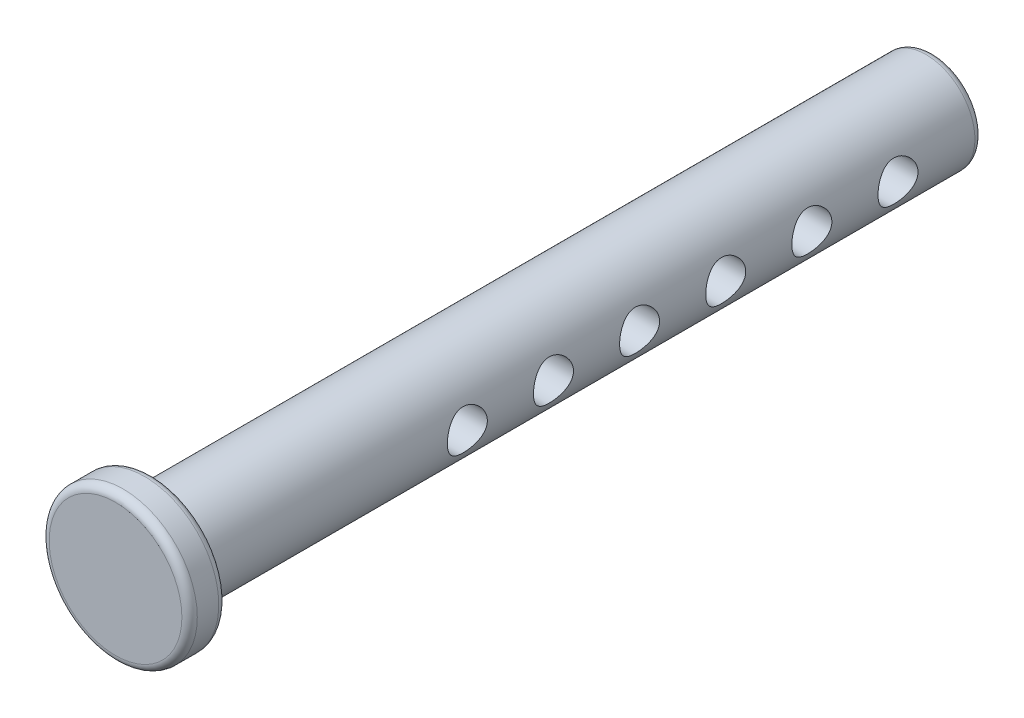
SolidWorks part; units mm, degrees
ref_plane "Front Plane" through (0, 0, 0) normal (1, 0, 0) x (0, 1, 0)
ref_plane "Top Plane" through (0, 0, 0) normal (0, 0, 1) x (0, 1, 0)
ref_plane "Right Plane" through (0, 0, 0) normal (0, 1, 0) x (-1, 0, 0)
sketch "Sketch1" plane through (0, 0, 0) normal (1, 0, 0) x (0, 1, 0)
  line L0 (0, 0) -> (4.815, 0)
  line L1 (4.815, 0) -> (4.815, -2.4)
  line L2 (4.815, -2.4) -> (3.175, -2.4)
  line L3 (3.175, -2.4) -> (3.175, -53.2)
  line L4 (3.175, -53.2) -> (0, -53.2)
  line L5 (0, -53.2) -> (0, 0)
  line L6 (0, -335.5768) -> (0, 16305.0472) construction
  dimension "D1" = 6.35
  dimension "D2" = 50.8
  dimension "D3" = 1.64
  dimension "D4" = 2.4
revolve "Revolve1" add sketch "Sketch1" angle 360 about L6
sketch "Sketch2" plane through (0, 0, 0) normal (1, 0, 0) x (0, 1, 0)
  line L0 (0, -47.7) -> (0, -42.1) construction
  line L1 (0, -42.1) -> (0, -36.5) construction
  line L2 (0, -36.5) -> (0, -30.9) construction
  line L3 (0, -30.9) -> (0, -25.3) construction
  line L4 (0, -25.3) -> (0, -19.7) construction
  line L5 (0, -47.7) -> (0, -49) construction
  line L6 (-3.175, -53.2) -> (3.175, -53.2) construction
  circle A0 centre (0, -47.7) radius 1.3
  circle A1 centre (0, -42.1) radius 1.3
  circle A3 centre (0, -25.3) radius 1.3
  circle A4 centre (0, -30.9) radius 1.3
  circle A6 centre (0, -36.5) radius 1.3
  circle A7 centre (0, -19.7) radius 1.3
  point P11 (0, -46.4)
  point P14 (0, -43.4)
  dimension "D1" = 2.6
  dimension "D2" = 4.2
  dimension "D3" = 3
extrude "Cut-Extrude1" cut sketch "Sketch2" against normal through all both and the other way through all
fillet "f7f" radius 0.5 2 edges at (-4.815, 0, -2.4) (-4.815, 0, 0)
fillet "Fillet2" radius 0.5 1 edges at (-3.175, 0, -53.2)
sketch "Sketch3" [suppressed] plane through (0, 0, 0) normal (1, 0, 0) x (0, 1, 0)
  line L0 (-3.175, -2.4) -> (-3.175, -52.7) construction
  line L1 (-3.175, -28.1) -> (3.175, -28.1)
  line L2 (-3.175, -28.1) -> (-3.175, -53.2)
  line L3 (-3.175, -53.2) -> (3.175, -53.2)
  line L4 (3.175, -28.1) -> (3.175, -53.2)
  line L5 (3.175, -52.7) -> (3.175, -2.4) construction
  line L6 (-2.675, -53.2) -> (2.675, -53.2) construction
  line L7 (0, -26.6) -> (0, -28.1) construction
  line L8 (0, -28.1) -> (0, -29.6) construction
  circle A2 centre (0, -30.9) radius 1.3 construction
  circle A3 centre (0, -25.3) radius 1.3 construction
  circle A4 centre (0, -25.3) radius 1.3 construction
extrude "Cut-Extrude2" [suppressed] cut sketch "Sketch3" against normal through all both and the other way through all
fillet "Fillet3" [suppressed] radius 0.5
sketch "Sketch4" [suppressed] plane through (0, 0, 0) normal (1, 0, 0) x (0, 1, 0)
  line L1 (-3.175, -22.5) -> (3.175, -22.5)
  line L2 (-3.175, -22.5) -> (-3.175, -53.2)
  line L3 (-3.175, -53.2) -> (3.175, -53.2)
  line L4 (3.175, -22.5) -> (3.175, -53.2)
  line L7 (0, -21) -> (0, -22.5) construction
  line L8 (0, -22.5) -> (0, -24) construction
  line L9 (3.175, -52.7) -> (3.175, -2.4) construction
  line L10 (-2.675, -53.2) -> (2.675, -53.2) construction
  line L11 (-3.175, -2.4) -> (-3.175, -52.7) construction
  circle A0 centre (0, -19.7) radius 1.3 construction
  circle A1 centre (0, -19.7) radius 1.3 construction
  circle A5 centre (0, -25.3) radius 1.3 construction
extrude "Cut-Extrude3" [suppressed] cut sketch "Sketch4" against normal through all both and the other way through all
fillet "Fillet5" [suppressed] radius 0.5
sketch "Sketch5" [suppressed] plane through (0, 0, 0) normal (1, 0, 0) x (0, 1, 0)
  line L0 (-3.175, -2.4) -> (-3.175, -52.7) construction
  line L1 (-3.175, -16.9) -> (3.175, -16.9)
  line L2 (-3.175, -16.9) -> (-3.175, -53.2)
  line L3 (-3.175, -53.2) -> (3.175, -53.2)
  line L4 (3.175, -16.9) -> (3.175, -53.2)
  line L5 (3.175, -52.7) -> (3.175, -2.4) construction
  line L6 (-2.675, -53.2) -> (2.675, -53.2) construction
  line L7 (0, -21) -> (0, -22.5) construction
  line L8 (0, -22.5) -> (0, -24) construction
  line L9 (0, -16.9) -> (0, -18.4) construction
  circle A0 centre (0, -19.7) radius 1.3 construction
  circle A1 centre (0, -19.7) radius 1.3 construction
  circle A2 centre (0, -25.3) radius 1.3 construction
extrude "Cut-Extrude4" [suppressed] cut sketch "Sketch5" against normal through all both and the other way through all
fillet "Fillet6" [suppressed] radius 0.5
sketch "Sketch6" [suppressed] plane through (0, 0, 0) normal (1, 0, 0) x (0, 1, 0)
  line L0 (-2.675, -16.9) -> (2.675, -16.9) construction
  circle A0 centre (0, -13.4) radius 1.3891
  dimension "D1" = 2.7781
  dimension "D2" = 3.5
extrude "Cut-Extrude5" [suppressed] cut sketch "Sketch6" against normal through all both and the other way through all
